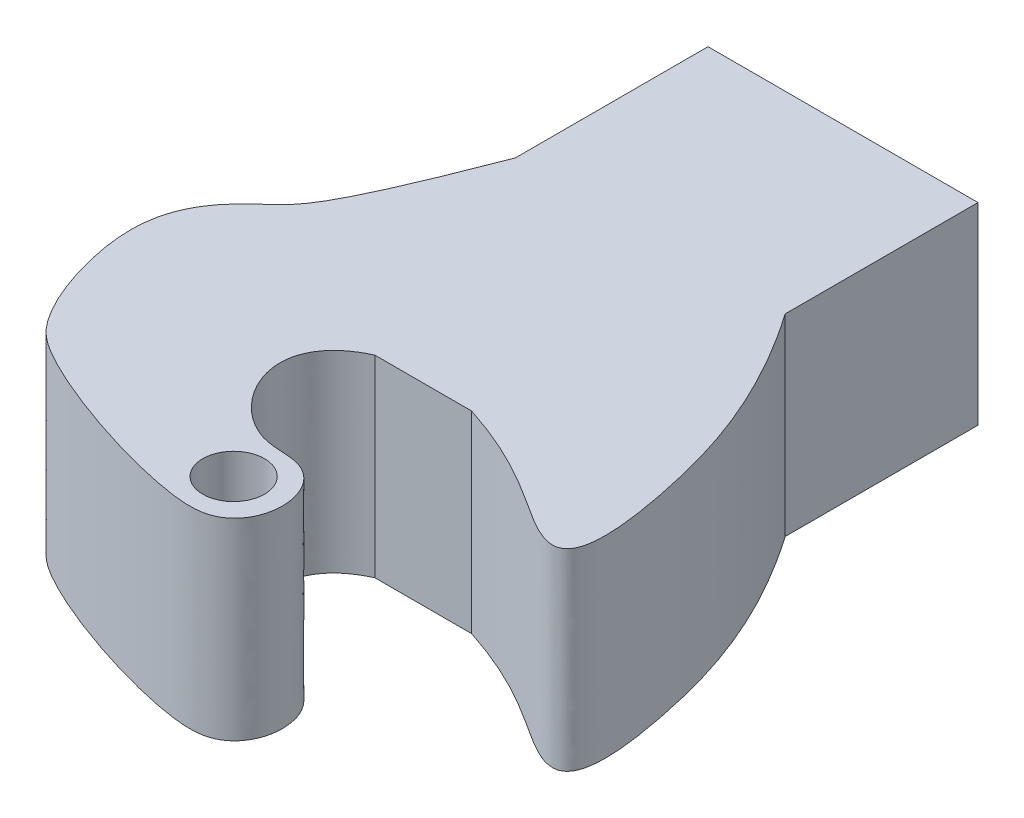
SolidWorks part; units mm, degrees
ref_plane "Front Plane" through (0, 0, 0) normal (0, 0, 1) x (1, 0, 0)
ref_plane "Top Plane" through (0, 0, 0) normal (0, 1, 0) x (1, 0, 0)
ref_plane "Right Plane" through (0, 0, 0) normal (1, 0, 0) x (0, 0, -1)
sketch "Sketch1" plane through (0, 0, 0) normal (0, 0, 1) x (1, 0, 0)
  line L1 (-175, -125) -> (175, -125)
  line L2 (-175, -125) -> (-175, 125)
  line L3 (-175, 125) -> (175, 125)
  line L4 (175, -125) -> (175, 125)
  line L5 (-175, -125) -> (175, 125) construction
  line L6 (-175, 125) -> (175, -125) construction
  point P0 (0, 0)
  dimension "D1" = 350
  dimension "D2" = 250
extrude "Boss-Extrude1" add sketch "Sketch1" along normal blind 250
sketch "Sketch2" plane through (0, 125, 0) normal (0, 1, 0) x (1, 0, 0)
  line L0 (-44.7617, -562.2572) -> (80.8956, -562.2572)
  line L1 (175, -250) -> (-175, -250) construction
  circle A0 centre (0, -790) radius 40
  spline S0 degree 3 poles (-175, -250) (-243.1587, -426.7435) (-279.7018, -458.6476) (-372.2893, -544.0302) (-313.3374, -725.6646) (-239.0277, -788.311) (-69.7669, -847.8415) (79.8248, -857.5881) (77.5308, -724.0344) (-68.9597, -737.752) (-144.3281, -608.0548) (-44.7617, -562.2572) knots 0 0 0 0 0.13738 0.290338 0.419115 0.452202 0.602431 0.641832 0.806809 0.844688 1 1 1 1
  spline S1 degree 3 poles (80.8956, -562.2572) (172.4313, -592.3163) (262.3143, -669.6138) (342.1335, -676.6406) (255.4196, -365.1699) (175, -250) knots 0 0 0 0 0.370061 0.815515 1 1 1 1
  line M3 (-175, -250) -> (175, -250)
  dimension "D1" = 540
  dimension "D2" = 80
extrude "Boss-Extrude2" add sketch "Sketch2" against normal up to vertex (250 mm away) contours L0 S1 S0 A0 M3
